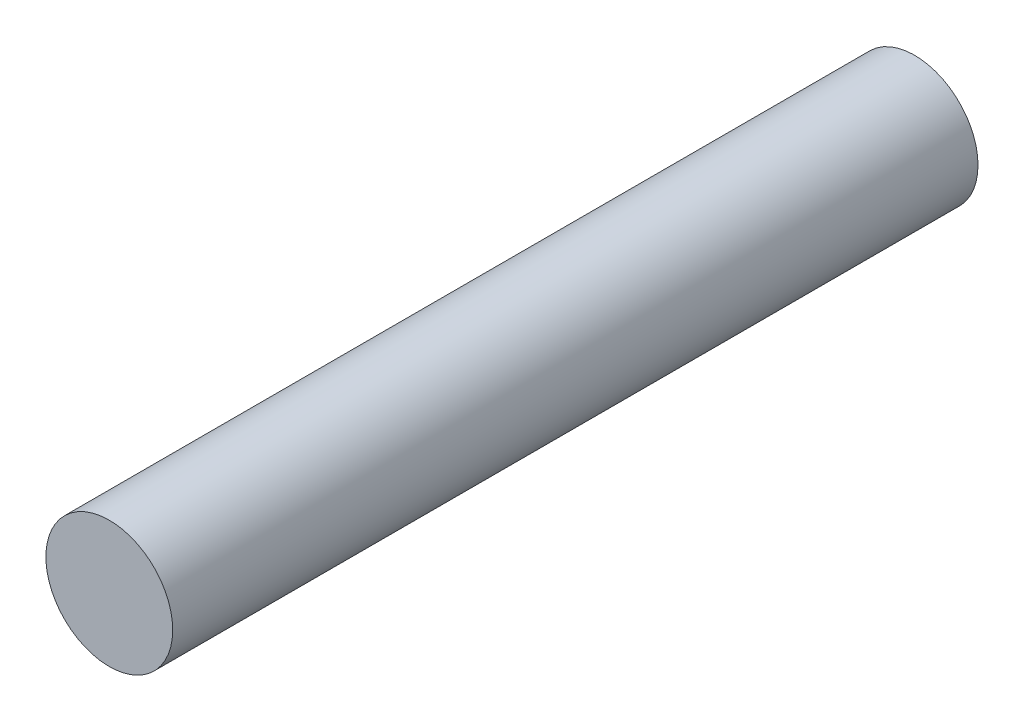
SolidWorks part; units mm, degrees
ref_plane "Front Plane" through (0, 0, 0) normal (0, 0, 1) x (1, 0, 0)
ref_plane "Top Plane" through (0, 0, 0) normal (0, 1, 0) x (1, 0, 0)
ref_plane "Right Plane" through (0, 0, 0) normal (1, 0, 0) x (0, 0, -1)
sketch "Sketch1" plane through (0, 0, 0) normal (0, 0, 1) x (1, 0, 0)
  circle A0 centre (0, 0) radius 1
  dimension "D1" = 2
extrude "Boss-Extrude1" add sketch "Sketch1" along normal blind 12.7
